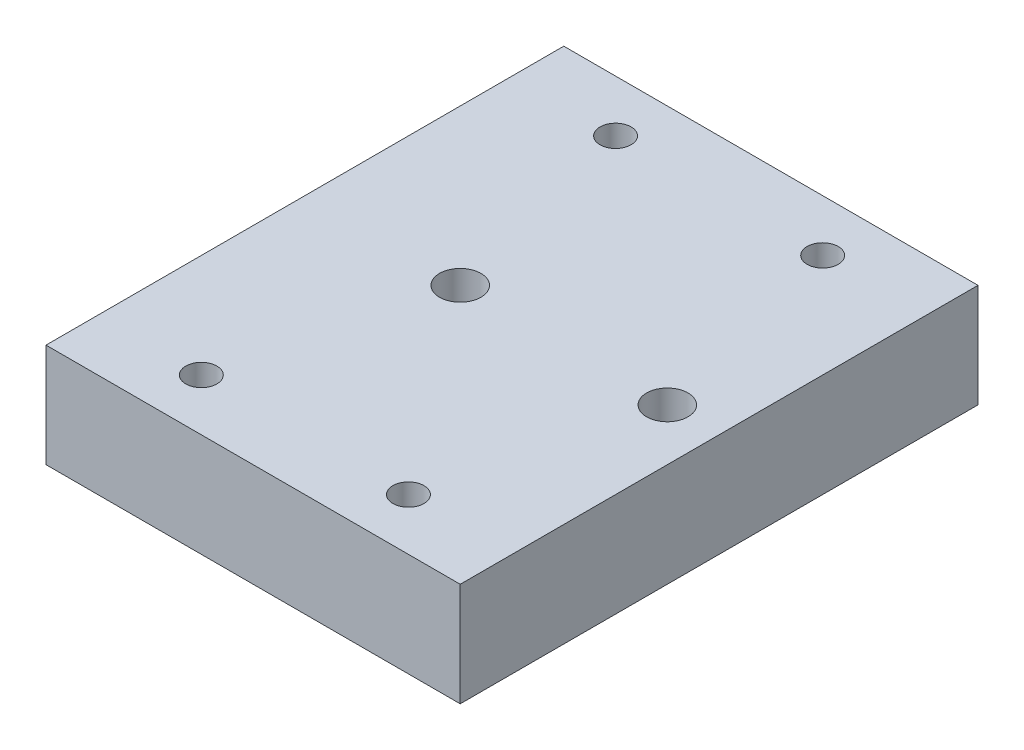
SolidWorks part; units mm, degrees
material "Сосна"
ref_plane "Спереди" through (0, 0, 0) normal (0, 0, 1) x (1, 0, 0)
ref_plane "Сверху" through (0, 0, 0) normal (0, 1, 0) x (1, 0, 0)
ref_plane "Справа" through (0, 0, 0) normal (1, 0, 0) x (0, 0, -1)
sketch "Эскиз1" plane through (0, 0, 0) normal (0, 1, 0) x (1, 0, 0)
  line L0 (0, 90) -> (80, 90) construction
  line L1 (0, 0) -> (80, 0)
  line L2 (0, 0) -> (0, 100)
  line L3 (0, 100) -> (80, 100)
  line L4 (80, 0) -> (80, 100)
  line L5 (0, 10) -> (80, 10) construction
  line L6 (0, 50) -> (80, 50) construction
  circle A0 centre (20, 90) radius 3
  circle A1 centre (60, 90) radius 3
  circle A2 centre (20, 10) radius 3
  circle A3 centre (60, 10) radius 3
  circle A4 centre (30, 50) radius 4
  circle A5 centre (70, 50) radius 4
  dimension "D5" = 6
  dimension "D6" = 6
  dimension "D7" = 6
  dimension "D8" = 6
  dimension "D13" = 8
  dimension "D14" = 8
  dimension "D1" = 100
  dimension "D2" = 80
  dimension "D3" = 10
  dimension "D4" = 10
  dimension "D9" = 20
  dimension "D10" = 20
  dimension "D11" = 20
  dimension "D12" = 20
  dimension "D15" = 30
  dimension "D16" = 40
extrude "Бобышка-Вытянуть1" add sketch "Эскиз1" along normal blind 20
